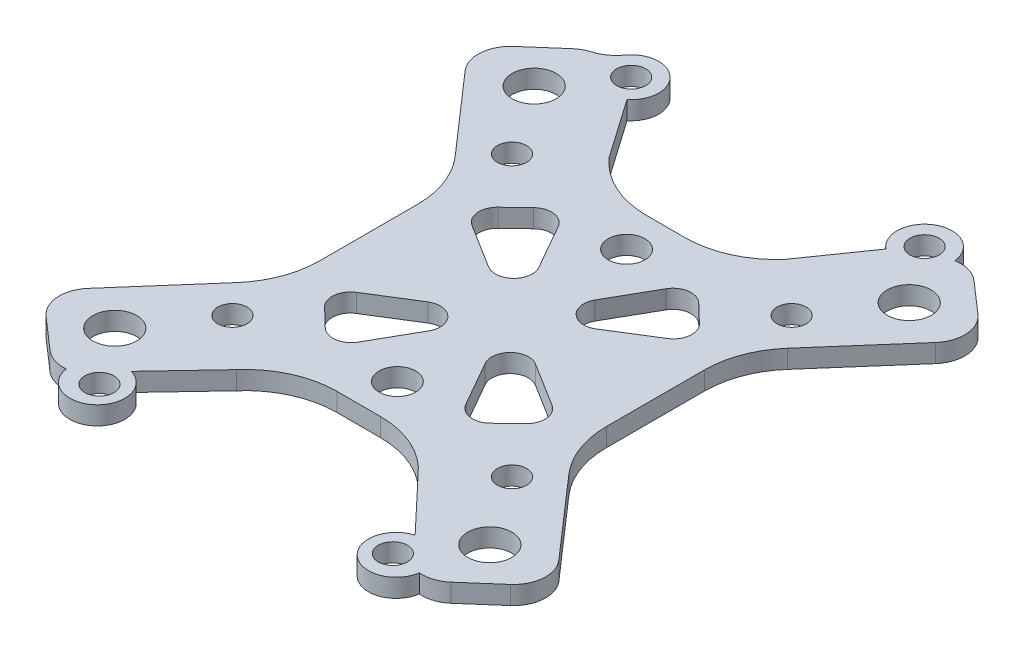
SolidWorks part; units mm, degrees
ref_plane "Alzado" through (0, 0, 0) normal (0, 0, 1) x (1, 0, 0)
ref_plane "Planta" through (0, 0, 0) normal (0, 1, 0) x (1, 0, 0)
ref_plane "Vista lateral" through (0, 0, 0) normal (1, 0, 0) x (0, 0, -1)
sketch "Croquis2" plane through (0, 0, 0) normal (0, 1, 0) x (1, 0, 0)
  line L0 (0, 0) -> (0, 10.4123) construction
  line L7 (-18.1147, -11.9133) -> (-25.6658, -20.5534)
  line L14 (-15.6443, 5.3327) -> (-15.6443, -5.3327)
  line L15 (-2.3687, -16.7202) -> (2.3687, -16.7202)
  line L16 (15.6443, 5.3327) -> (15.6443, -5.3327)
  line L17 (-13.8775, 14.4472) -> (-9.9975, 10.4079) construction
  line L18 (-2.0794, 16.7817) -> (2.0794, 16.7817)
  line L20 (-25.3337, -25.492) -> (-21.87, -28.5191)
  line L21 (18.1147, -11.9133) -> (25.6658, -20.5534)
  line L23 (25.3337, -25.492) -> (21.87, -28.5191)
  line L24 (25.3337, 25.492) -> (21.87, 28.5191)
  line L25 (9.6091, 20.2011) -> (14.1192, 26.6628)
  line L26 (18.1147, 11.9133) -> (25.6658, 20.5534)
  line L27 (-25.3337, 25.492) -> (-21.87, 28.5191)
  line L30 (-18.1147, 11.9133) -> (-25.6658, 20.5534)
  line L31 (-9.6091, 20.2011) -> (-14.1192, 26.6628)
  line L33 (9.8983, -20.1396) -> (15.4814, -26.0493)
  line L34 (-9.8983, -20.1396) -> (-15.4814, -26.0493)
  line L37 (0, 0) -> (-15.6443, 0) construction
  line L38 (-8.9971, 11.3688) -> (-10.9978, 9.447)
  line L39 (-10.671, 6.3078) -> (-5.8711, 3.3132)
  line L40 (-5.8736, 10.916) -> (-3.0744, 5.9996)
  line L41 (5.8736, 10.916) -> (3.0744, 5.9996)
  line L42 (10.671, 6.3078) -> (5.8711, 3.3132)
  line L43 (8.9971, 11.3688) -> (10.9978, 9.447)
  line L45 (8.9971, -11.3688) -> (10.9978, -9.447)
  line L46 (10.671, -6.3078) -> (5.8711, -3.3132)
  line L47 (5.8736, -10.916) -> (3.0744, -5.9996)
  line L48 (-5.8736, -10.916) -> (-3.0744, -5.9996)
  line L49 (-10.671, -6.3078) -> (-5.8711, -3.3132)
  line L50 (-8.9971, -11.3688) -> (-10.9978, -9.447)
  arc A19 (-19.2581, -29.3701) -> (-21.87, -28.5191) centre (-19.5668, -25.8837) cw
  arc A20 (-25.3337, -25.492) -> (-25.6658, -20.5534) centre (-23.0305, -22.8566) cw
  arc A21 (25.3337, -25.492) -> (25.6658, -20.5534) centre (23.0305, -22.8566) ccw
  arc A22 (19.2581, -29.3701) -> (21.87, -28.5191) centre (19.5668, -25.8837) ccw
  arc A23 (18.9829, 29.3199) -> (21.87, 28.5191) centre (19.581, 25.8714) cw
  arc A24 (25.3337, 25.492) -> (25.6658, 20.5534) centre (23.0305, 22.8566) cw
  arc A25 (-25.3337, 25.492) -> (-25.6658, 20.5534) centre (-23.0305, 22.8566) ccw
  arc A26 (-20.5688, 29.2291) -> (-21.87, 28.5191) centre (-19.581, 25.8714) ccw
  circle A43 centre (-16, 29) radius 1.5875
  arc A44 (-14.1192, 26.6628) -> (-18.4419, 30.7428) centre (-16, 29) ccw
  circle A45 centre (16, 29) radius 1.5875
  arc A48 (9.6091, 20.2011) -> (2.0794, 16.7817) centre (2.0794, 26.7817) cw
  arc A50 (-3.0744, 5.9996) -> (-5.8711, 3.3132) centre (-4.8125, 5.01) cw
  arc A51 (-8.9971, 11.3688) -> (-5.8736, 10.916) centre (-7.6116, 9.9264) cw
  arc A52 (-10.9978, 9.447) -> (-10.671, 6.3078) centre (-9.6123, 8.0046) ccw
  arc A53 (10.9978, 9.447) -> (10.671, 6.3078) centre (9.6123, 8.0046) cw
  arc A54 (8.9971, 11.3688) -> (5.8736, 10.916) centre (7.6116, 9.9264) ccw
  arc A55 (3.0744, 5.9996) -> (5.8711, 3.3132) centre (4.8125, 5.01) ccw
  arc A56 (8.9971, -11.3688) -> (5.8736, -10.916) centre (7.6116, -9.9264) cw
  arc A57 (-8.9971, -11.3688) -> (-5.8736, -10.916) centre (-7.6116, -9.9264) ccw
  arc A58 (3.0744, -5.9996) -> (5.8711, -3.3132) centre (4.8125, -5.01) cw
  arc A59 (10.9978, -9.447) -> (10.671, -6.3078) centre (9.6123, -8.0046) ccw
  arc A60 (-10.9978, -9.447) -> (-10.671, -6.3078) centre (-9.6123, -8.0046) cw
  arc A61 (-3.0744, -5.9996) -> (-5.8711, -3.3132) centre (-4.8125, -5.01) ccw
  circle A62 centre (0, 12.4971) radius 2
  circle A63 centre (0, -12.4971) radius 2
  arc A64 (-18.1147, 11.9133) -> (-15.6443, 5.3327) centre (-25.6443, 5.3327) cw
  arc A65 (-15.6443, -5.3327) -> (-18.1147, -11.9133) centre (-25.6443, -5.3327) cw
  arc A66 (-2.3687, -16.7202) -> (-9.8983, -20.1396) centre (-2.3687, -26.7202) ccw
  arc A67 (2.3687, -16.7202) -> (9.8983, -20.1396) centre (2.3687, -26.7202) cw
  arc A68 (15.6443, -5.3327) -> (18.1147, -11.9133) centre (25.6443, -5.3327) ccw
  arc A69 (18.1147, 11.9133) -> (15.6443, 5.3327) centre (25.6443, 5.3327) ccw
  arc A70 (14.1192, 26.6628) -> (18.9829, 29.3199) centre (16, 29) cw
  arc A71 (-9.6091, 20.2011) -> (-2.0794, 16.7817) centre (-2.0794, 26.7817) ccw
  arc A73 (15.4814, -26.0493) -> (19.2581, -29.3701) centre (16.2893, -28.9384) ccw
  circle A77 centre (-15.25, 15.25) radius 1.59
  arc A89 (-15.4814, -26.0493) -> (-19.2581, -29.3701) centre (-16.2893, -28.9384) cw
  circle A96 centre (-15.25, -15.25) radius 1.59
  circle A97 centre (-20.4532, 22.8733) radius 1.5974
  circle A98 centre (-20.4532, 22.8733) radius 2.4
  circle A99 centre (20.4532, 22.8733) radius 1.5974
  circle A100 centre (20.4532, 22.8733) radius 2.4
  circle A101 centre (20.4532, -22.8733) radius 1.5974
  circle A102 centre (20.4532, -22.8733) radius 2.4
  circle A103 centre (-20.4532, -22.8733) radius 1.5974
  circle A104 centre (-20.4532, -22.8733) radius 2.4
  arc A105 (-18.4419, 30.7428) -> (-20.5688, 29.2291) centre (-21.6977, 33.0665) cw
  circle A106 centre (15.25, -15.25) radius 1.59
  circle A107 centre (15.25, 15.25) radius 1.59
  circle A108 centre (-16, -29) radius 1.5875
  circle A109 centre (16, -29) radius 1.5875
  point P22 (-19.2347, -30.8223)
  point P25 (-27.9691, -23.1888)
  point P34 (27.9691, -23.1888)
  point P35 (19.2347, -30.8223)
  point P53 (19.2347, 30.8223)
  point P54 (-27.9691, 23.1888)
  point P55 (-19.2347, 30.8223)
  point P64 (-18.9829, 29.3199)
  point P89 (-9.9975, 10.4079)
  point P92 (0.8383, -0.8727)
  point P96 (-7.1445, 13.1483)
  point P99 (-12.8504, 7.6675)
  point P112 (12.8504, 7.6675)
  point P113 (7.1445, 13.1483)
  point P114 (9.9975, 10.4079)
  point P135 (9.9975, -10.4079)
  point P136 (12.8504, -7.6675)
  point P137 (-12.8504, -7.6675)
  point P138 (-9.9975, -10.4079)
  point P143 (-15.6443, 9.0867)
  point P146 (-15.6443, -9.0867)
  point P149 (-6.9099, -16.7202)
  point P152 (6.9099, -16.7202)
  point P155 (15.6443, -9.0867)
  point P158 (15.6443, 9.0867)
  dimension "D3" = 3.5
  dimension "D5" = 15.25
  dimension "D2" = 3.18
  dimension "D9" = 13.8199
  dimension "D10" = 3.175
  dimension "D12" = 10
  dimension "D13" = 6
  dimension "D8" = 2
  dimension "D11" = 4
  dimension "D4" = 4.8
  dimension "D6" = 4
  dimension "D14" = 15.25
  dimension "D15" = 16
  dimension "D16" = 29
extrude "Saliente-Extruir1" add sketch "Croquis2" along normal blind 2
